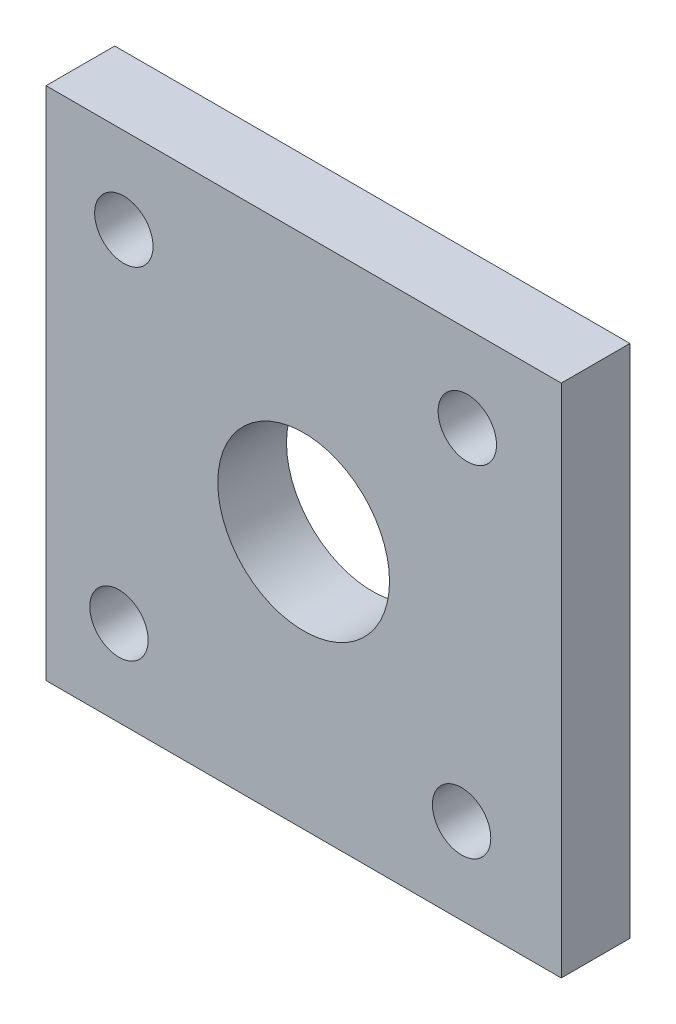
SolidWorks part; units mm, degrees
ref_plane "Front Plane" through (0, 0, 0) normal (0, 0, 1) x (1, 0, 0)
ref_plane "Top Plane" through (0, 0, 0) normal (0, 1, 0) x (1, 0, 0)
ref_plane "Right Plane" through (0, 0, 0) normal (1, 0, 0) x (0, 0, -1)
sketch "Sketch1" plane through (0, 0, 0) normal (0, 0, 1) x (1, 0, 0)
  line L1 (-13.8772, 14.5393) -> (16.1228, 14.5393)
  line L2 (-13.8772, 14.5393) -> (-13.8772, -15.4607)
  line L3 (-13.8772, -15.4607) -> (16.1228, -15.4607)
  line L4 (16.1228, 14.5393) -> (16.1228, -15.4607)
  dimension "D1" = 30
  dimension "D2" = 30
extrude "Boss-Extrude1" add sketch "Sketch1" along normal blind 4
sketch "Sketch2" plane through (0, 0, 4) normal (0, 0, 1) x (1, 0, 0)
  line L0 (-13.8772, 14.5393) -> (-13.8772, -15.4607) construction
  line L1 (16.1228, 14.5393) -> (-13.8772, 14.5393) construction
  circle A0 centre (1.1228, -0.4607) radius 5
  dimension "D1" = 10
  dimension "D2" = 15
  dimension "D3" = 15
extrude "Cut-Extrude1" cut sketch "Sketch2" against normal through all
sketch "Sketch3" plane through (0, 0, 4) normal (0, 0, 1) x (1, 0, 0)
  line L0 (-13.8772, -15.4607) -> (16.1228, -15.4607) construction
  circle A0 centre (-9.348, 9.5393) radius 1.7
  circle A1 centre (10.652, 9.5393) radius 1.7
  circle A2 centre (-9.631, -10.4607) radius 1.7
  circle A3 centre (10.3202, -10.4607) radius 1.7
  dimension "D1" = 3.4
  dimension "D2" = 3.4
  dimension "D3" = 3.4
  dimension "D4" = 3.4
  dimension "D6" = 5
  dimension "D8" = 5
  dimension "D9" = 20
  dimension "D5" = 20
  dimension "D7" = 20
extrude "Cut-Extrude2" cut sketch "Sketch3" against normal through all
